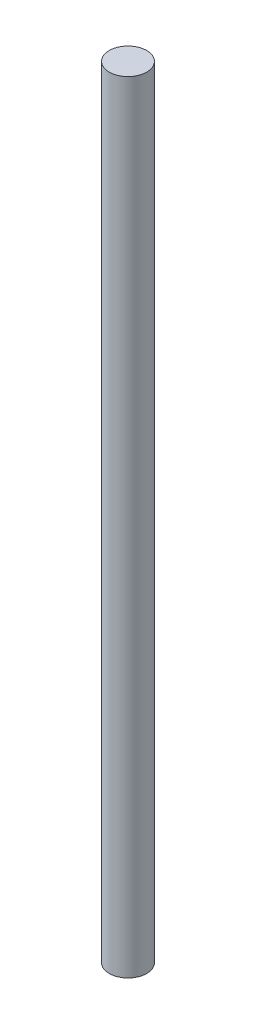
SolidWorks part; units mm, degrees
ref_plane "Front Plane" through (0, 0, 0) normal (0, 0, 1) x (1, 0, 0)
ref_plane "Top Plane" through (0, 0, 0) normal (0, 1, 0) x (1, 0, 0)
ref_plane "Right Plane" through (0, 0, 0) normal (1, 0, 0) x (0, 0, -1)
sketch "Sketch2" plane through (0, 0, 0) normal (0, 1, 0) x (1, 0, 0)
  circle A0 centre (0, 0) radius 237.5
  dimension "D1" = 475
extrude "Boss-Extrude1" add sketch "Sketch2" along normal blind 9900
